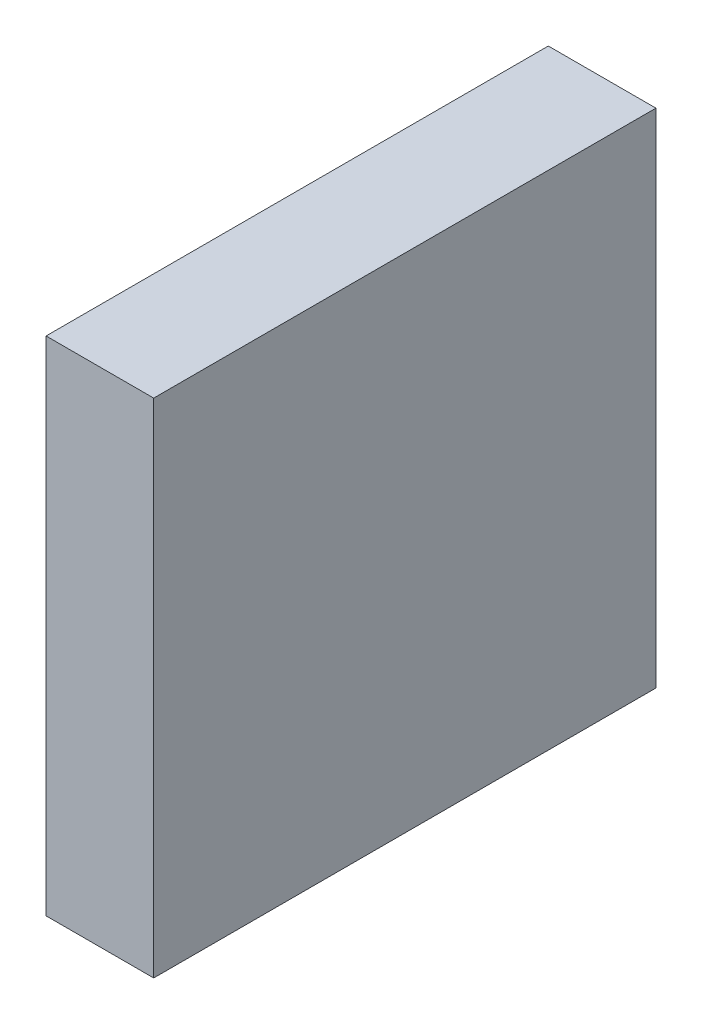
SolidWorks part; units mm, degrees
ref_plane "Front Plane" through (0, 0, 0) normal (0, 0, 1) x (1, 0, 0)
ref_plane "Top Plane" through (0, 0, 0) normal (0, 1, 0) x (1, 0, 0)
ref_plane "Right Plane" through (0, 0, 0) normal (1, 0, 0) x (0, 0, -1)
other "Configuration Table"
sketch "Sketch1" plane through (0, 0, 0) normal (0, 0, 1) x (1, 0, 0)
  line L1 (172.5, 480) -> (202.5, 480)
  line L2 (172.5, 480) -> (172.5, 620)
  line L3 (172.5, 620) -> (202.5, 620)
  line L4 (202.5, 480) -> (202.5, 620)
extrude "TOPPING_evap_fan_1_1" add sketch "Sketch1" against normal blind 140 from offset 330 separate body
